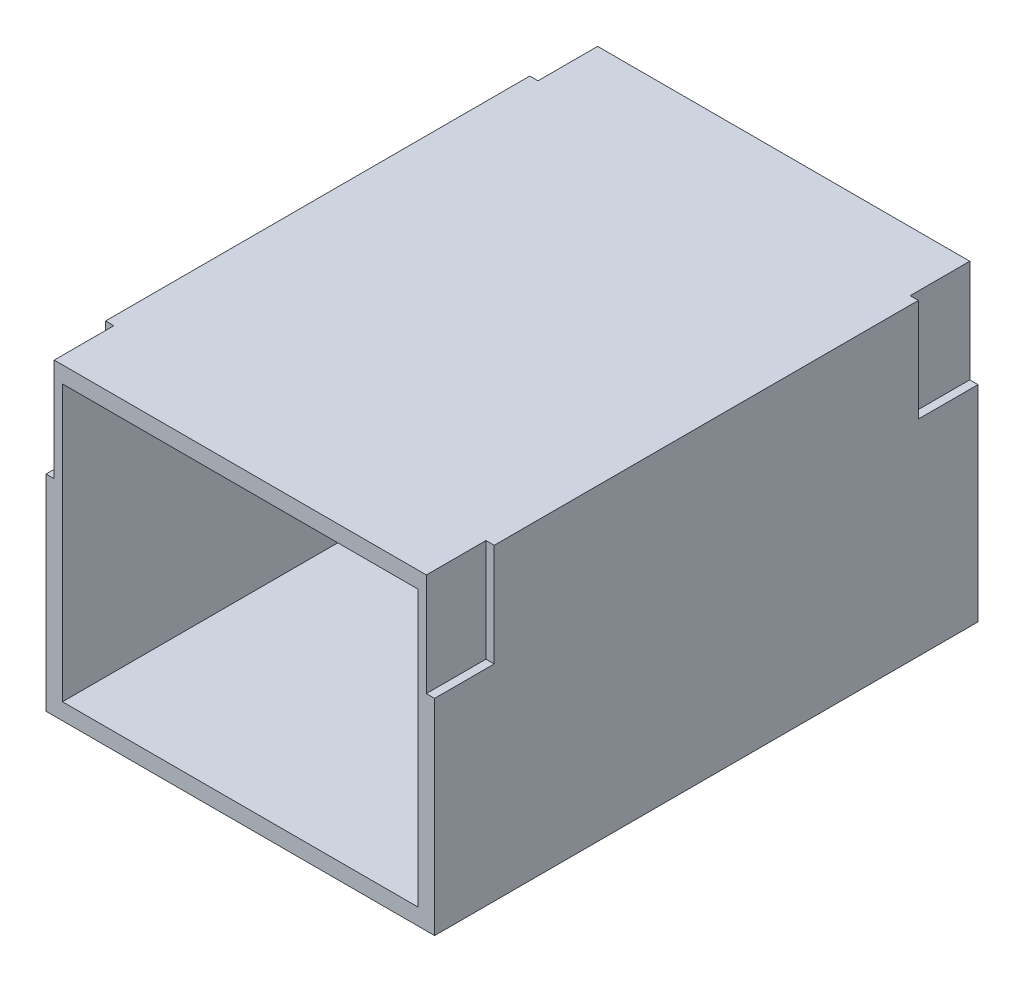
SolidWorks part; units mm, degrees
ref_plane "Front Plane" through (0, 0, 0) normal (0, 0, 1) x (1, 0, 0)
ref_plane "Top Plane" through (0, 0, 0) normal (0, 1, 0) x (1, 0, 0)
ref_plane "Right Plane" through (0, 0, 0) normal (1, 0, 0) x (0, 0, -1)
sketch "Sketch2" plane through (0, 0, 0) normal (0, 0, 1) x (1, 0, 0)
  line L0 (37.465, 59.436) -> (37.465, 0) construction
  line L1 (0, 0) -> (74.93, 0)
  line L2 (0, 0) -> (0, 59.436)
  line L3 (0, 59.436) -> (74.93, 59.436)
  line L4 (74.93, 0) -> (74.93, 59.436)
  line L6 (71.755, 56.261) -> (3.175, 56.261)
  line L7 (71.755, 56.261) -> (71.755, 3.175)
  line L8 (71.755, 3.175) -> (3.175, 3.175)
  line L9 (3.175, 56.261) -> (3.175, 3.175)
  line L10 (71.755, 56.261) -> (3.175, 3.175) construction
  line L11 (71.755, 3.175) -> (3.175, 56.261) construction
  point P5 (37.465, 29.718)
  dimension "D1" = 68.58
  dimension "D2" = 59.436
  dimension "D3" = 3.175
  dimension "D4" = 3.175
extrude "Extrude1" add sketch "Sketch2" against normal blind 104.775
sketch "Sketch4" plane through (0, 59.436, 0) normal (0, 1, 0) x (-1, 0, 0)
  line L0 (0, -52.3875) -> (0, -11.4935) construction
  line L1 (0, -104.775) -> (0, 0) construction
  line L2 (0, -52.3875) -> (0, -93.2815) construction
  line L3 (0, -93.2815) -> (-1.5875, -93.2815) construction
  line L4 (0, -11.4935) -> (-1.5875, -11.4935) construction
  line L5 (0, -52.3875) -> (-74.93, -52.3875) construction
  line L6 (-74.93, -104.775) -> (-74.93, 0) construction
  line L7 (-74.93, -93.2815) -> (-73.3425, -93.2815) construction
  line L8 (-74.93, -11.4935) -> (-73.3425, -11.4935) construction
  line L9 (-74.93, 0) -> (0, 0) construction
  line L10 (-1.5875, -93.2815) -> (0, -93.2815)
  line L11 (-1.5875, -93.2815) -> (-1.5875, -104.775)
  line L12 (-1.5875, -104.775) -> (0, -104.775)
  line L13 (0, -93.2815) -> (0, -104.775)
  line L14 (-1.5875, -11.4935) -> (0, -11.4935)
  line L15 (-1.5875, -11.4935) -> (-1.5875, 0)
  line L16 (-1.5875, 0) -> (0, 0)
  line L17 (0, -11.4935) -> (0, 0)
  line L18 (-73.3425, -11.4935) -> (-74.93, -11.4935)
  line L19 (-73.3425, -11.4935) -> (-73.3425, 0)
  line L20 (-73.3425, 0) -> (-74.93, 0)
  line L21 (-74.93, -11.4935) -> (-74.93, 0)
  line L22 (-74.93, -93.2815) -> (-74.93, -11.4935) construction
  line L23 (-73.3425, -93.2815) -> (-74.93, -93.2815)
  line L24 (-73.3425, -93.2815) -> (-73.3425, -104.775)
  line L25 (-73.3425, -104.775) -> (-74.93, -104.775)
  line L26 (-74.93, -93.2815) -> (-74.93, -104.775)
  dimension "D1" = 40.894
  dimension "D2" = 1.5875
  dimension "D3" = 40.894
extrude "Extrude2" cut sketch "Sketch4" against normal blind 19.812
sketch "Sketch6" plane through (0, 0, 0) normal (0, 0, 1) x (1, 0, 0)
  line L3 (37.465, 59.436) -> (37.465, 0) construction
  line L4 (73.3425, 59.436) -> (1.5875, 59.436) construction
  line L5 (0, 0) -> (74.93, 0) construction
sketch "Sketch7" plane through (0, 0, 0) normal (0, 0, 1) x (1, 0, 0)
  line L0 (74.93, 29.718) -> (0, 29.718) construction
  line L1 (74.93, 0) -> (74.93, 39.624) construction
  line L2 (0, 39.624) -> (0, 0) construction
sketch "Sketch9" plane through (0, 0, 0) normal (0, 0, 1) x (1, 0, 0)
ref_plane "Plane2" through (0, 0, -52.3875) normal (0, 0, -1) x (-1, 0, 0)
sketch "Sketch12" plane through (0, 59.436, 0) normal (0, 1, 0) x (-1, 0, 0)
  line L0 (-37.465, 0) -> (-37.465, -104.775) construction
  line L1 (-73.3425, -104.775) -> (-1.5875, -104.775) construction
ref_plane "Plane3" through (37.465, 0, 0) normal (1, 0, 0) x (0, 0, -1)
sketch "Sketch13" plane through (0, 0, -104.775) normal (0, 0, -1) x (-1, 0, 0)
  line L1 (-71.755, 56.261) -> (-3.175, 56.261)
  line L2 (-71.755, 56.261) -> (-71.755, 3.175)
  line L3 (-71.755, 3.175) -> (-3.175, 3.175)
  line L4 (-3.175, 56.261) -> (-3.175, 3.175)
extrude "Extrude4" add sketch "Sketch13" against normal blind 1.5875
equation "\"D3@Sketch4\" = \"D1@Sketch4\""
